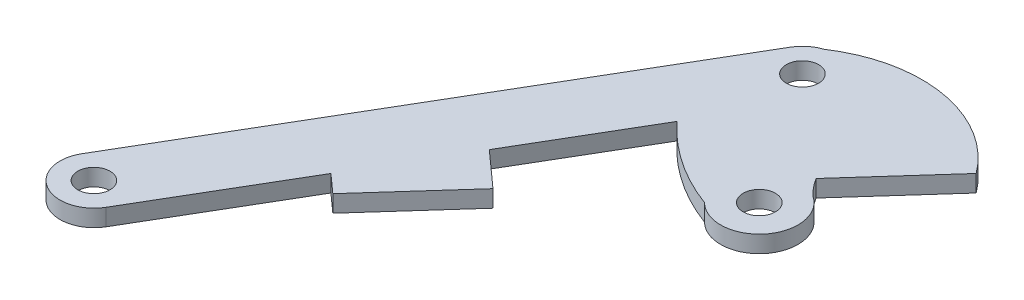
SolidWorks part; units mm, degrees
material "Cedro"
ref_plane "Alzado" through (0, 0, 0) normal (0, 0, 1) x (1, 0, 0)
ref_plane "Planta" through (0, 0, 0) normal (0, 1, 0) x (1, 0, 0)
ref_plane "Vista lateral" through (0, 0, 0) normal (1, 0, 0) x (0, 0, -1)
sketch "Croquis1" plane through (0, 0, 0) normal (0, 1, 0) x (1, 0, 0)
  line L0 (2.7441, 395.2665) -> (-229.13, 0) construction
  line L3 (28.6203, 380.0868) -> (-203.2538, -15.1797)
  line L4 (-23.1321, 410.4462) -> (-255.0062, 15.1797)
  arc A3 (28.6203, 380.0868) -> (-23.1321, 410.4462) centre (2.7441, 395.2665) ccw
  arc A4 (-255.0062, 15.1797) -> (-203.2538, -15.1797) centre (-229.13, 0) ccw
  point P2 (0, 0)
  point P4 (-113.193, 197.6333)
  dimension "D2" = 30
  dimension "D1" = 231.8741
extrude "Saliente-Extruir1" add sketch "Croquis1" along normal blind 15
sketch "Croquis3" plane through (0, 15, 0) normal (0, 1, 0) x (1, 0, 0)
  circle A0 centre (-229.13, 0) radius 14.29
  circle A1 centre (2.7441, 395.2665) radius 14.29
  dimension "D1" = 28.58
  dimension "D2" = 28.58
extrude "Cortar-Extruir2" cut sketch "Croquis3" against normal through all
sketch "Croquis4" plane through (0, 15, 0) normal (0, 1, 0) x (1, 0, 0)
  line L0 (-113.2889, 95.6285) -> (-129.646, 110.2966)
  line L1 (-203.2538, -15.1797) -> (28.6203, 380.0868) construction
  line L2 (-129.646, 110.2966) -> (-77.8157, 198.6497)
  line L3 (-46.2717, 170.3629) -> (-35.1042, 160.3486) construction
  line L4 (-77.8157, 198.6497) -> (-46.2717, 170.3629)
  line L5 (-46.2717, 170.3629) -> (-113.2889, 95.6285)
extrude "Saliente-Extruir2" add sketch "Croquis4" against normal through all
sketch "Croquis5" plane through (0, 15, 0) normal (0, 1, 0) x (1, 0, 0)
  line L0 (155.9528, 395.874) -> (88.9356, 321.1396)
  line L1 (-23.1321, 410.4462) -> (17.0937, 410.4462)
  line L2 (17.0937, 410.4462) -> (21.6145, 387.9873)
  line L3 (21.6145, 387.9873) -> (11.4593, 350.8332)
  arc A0 (88.9356, 321.1396) -> (11.4593, 350.8332) centre (21.6145, 261.408) ccw
  arc A1 (-6.4312, 423.829) -> (155.9528, 395.874) centre (59.9583, 323.8668) cw
  arc A2 (-6.4312, 423.829) -> (-23.1321, 410.4462) centre (2.7441, 395.2665) ccw
extrude "Saliente-Extruir3" add sketch "Croquis5" against normal through all
sketch "Croquis6" plane through (0, 0, 0) normal (0, -1, 0) x (-1, 0, 0)
  line L0 (-82.2649, 277.5665) -> (-82.2649, 361.0181) construction
  line L1 (-82.2649, 361.0181) -> (-82.2649, 277.5665) construction
  line L2 (-82.2649, 277.5665) -> (-160.3466, 355.6482) construction
  line L3 (-82.2649, 277.5665) -> (-18.4706, 213.7722) construction
  line L4 (77.8157, 198.6497) -> (-11.4593, 350.8332) construction
  line L5 (16.3701, 303.3935) -> (-7.0318, 366.1854)
  line L6 (-7.0318, 366.1854) -> (-88.9356, 345.8949)
  line L7 (-88.9356, 345.8949) -> (-88.9356, 321.1396)
  circle A0 centre (-82.2649, 277.5665) radius 14.29
  arc A1 (-101.5413, 305.9253) -> (-58.0182, 253.3198) centre (-82.2649, 277.5665) ccw
  arc A2 (-101.5413, 305.9253) -> (-88.9356, 321.1396) centre (-148.6012, 357.7459) ccw
  arc A3 (-58.0182, 253.3198) -> (16.3701, 303.3935) centre (-123.9259, 431.5224) ccw
  dimension "D1" = 20
  dimension "D2" = 28.58
  dimension "D5" = 190
  dimension "D6" = 70
  dimension "D3" = 45
  dimension "D4" = 180
  dimension "D7" = 55
extrude "Saliente-Extruir4" add sketch "Croquis6" against normal up to surface (15 mm away) up to face at (-55.0663, 15, -226.7691)
